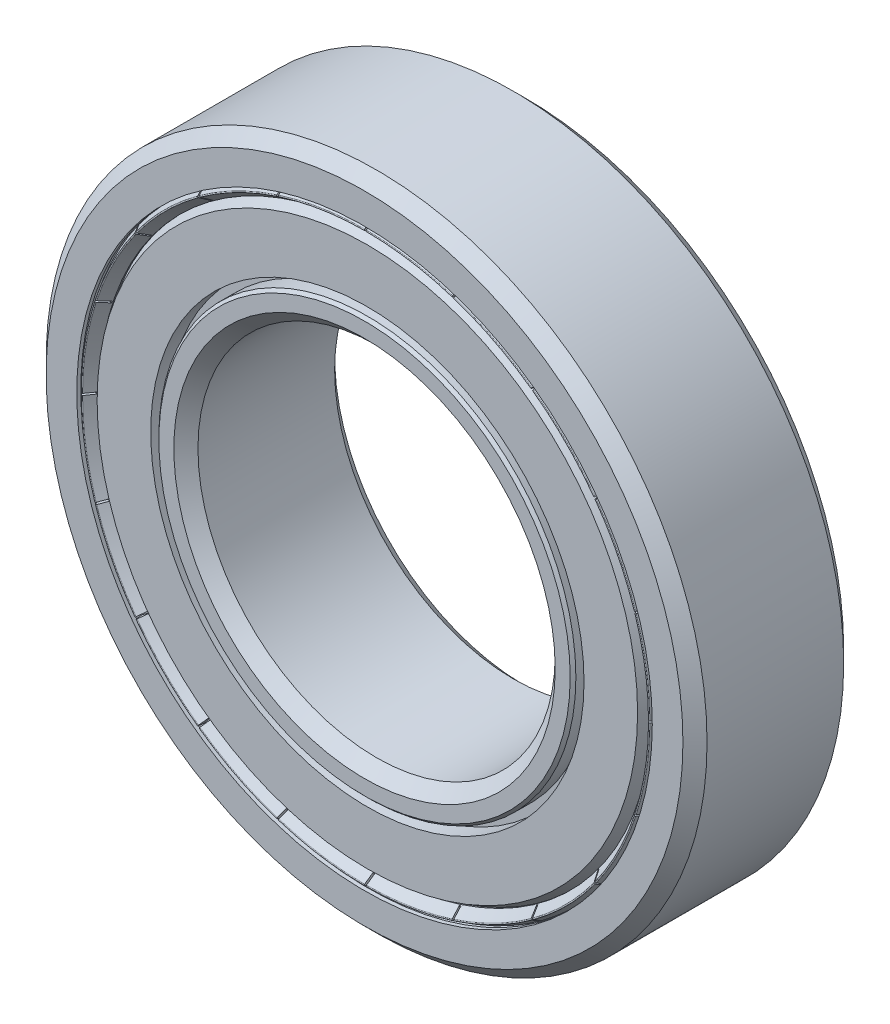
SolidWorks part; units mm, degrees
ref_plane "Front Plane" through (0, 0, 0) normal (0, 0, 1) x (1, 0, 0)
ref_plane "Top Plane" through (0, 0, 0) normal (0, 1, 0) x (1, 0, 0)
ref_plane "Right Plane" through (0, 0, 0) normal (1, 0, 0) x (0, 0, -1)
sketch "Sketch1" plane through (0, 0, 0) normal (0, 0, 1) x (1, 0, 0)
  circle A0 centre (0, 0) radius 10
  circle A1 centre (0, 0) radius 18.5
  dimension "OD" = 37
  dimension "ID" = 20
sketch "Sketch2" plane through (0, 0, 0) normal (1, 0, 0) x (0, 0, -1)
  line L0 (-4.5, 18.5) -> (4.5, 18.5)
  line L1 (-4.5, 10) -> (-4.5, -10) construction
  line L2 (4.5, 18.5) -> (4.5, -18.5) construction
  line L3 (-4.5, 0) -> (4.5, 0) construction
  line L6 (0, 18.5) -> (0, 10) construction
  circle A0 centre (0, 14.25) radius 2.975 construction
  point P8 (0, 18.5)
  dimension "Approx. Ball Dia." = 5.95
  dimension "Width" = 9
  dimension "For Shaft Diameter" = 20
  dimension "For Housing ID" = 37
sketch "Sketch3" plane through (0, 0, 0) normal (1, 0, 0) x (0, 0, -1)
  line L0 (0, 0) -> (0, 20) construction
  line L1 (-4.5, 10) -> (-4.5, -10) construction
  line L2 (3.825, 18.5) -> (-3.825, 18.5)
  line L3 (-3.825, 18.5) -> (-4.5, 17.825)
  line L4 (-4.5, 17.825) -> (-4.5, 16.1097)
  line L5 (-4.5, 16.1097) -> (-4.275, 16.1097)
  line L6 (-4.275, 16.1097) -> (-4.275, 16.6673)
  line L7 (-4.275, 16.6673) -> (-4.1159, 16.8264)
  line L8 (-4.1159, 16.8264) -> (-1.4875, 16.8264)
  line L10 (-4.5, 18.5) -> (4.5, 18.5) construction
  line L12 (-4.275, 16.6673) -> (-4.275, 17.225) construction
  line L13 (4.1159, 16.8264) -> (1.4875, 16.8264)
  line L14 (4.275, 16.6673) -> (4.1159, 16.8264)
  line L15 (4.275, 16.1097) -> (4.275, 16.6673)
  line L16 (4.5, 16.1097) -> (4.275, 16.1097)
  line L17 (4.5, 17.825) -> (4.5, 16.1097)
  line L18 (3.825, 18.5) -> (4.5, 17.825)
  line L19 (3.825, 10) -> (-3.825, 10)
  line L20 (-3.825, 10) -> (-4.5, 10.675)
  line L21 (-4.5, 10.675) -> (-4.5, 11.5145)
  line L22 (-4.5, 11.5145) -> (-4.3409, 11.6736)
  line L23 (-4.3409, 11.6736) -> (-1.4875, 11.6736)
  line L25 (4.3409, 11.6736) -> (1.4875, 11.6736)
  line L26 (4.5, 11.5145) -> (4.3409, 11.6736)
  line L27 (4.5, 10.675) -> (4.5, 11.5145)
  line L28 (3.825, 10) -> (4.5, 10.675)
  circle A2 centre (0, 14.25) radius 2.975 construction
  arc A3 (-1.4875, 16.8264) -> (1.4875, 16.8264) centre (0, 14.25) cw
  arc A4 (-1.4875, 11.6736) -> (1.4875, 11.6736) centre (0, 14.25) ccw
  point P5 (0, 17.225)
  point P31 (0, 18.5)
  point P37 (0, 10)
  dimension "D1" = 45
  dimension "D2" = 0.225
  dimension "D3" = 2.975
  dimension "D4" = 0.675
revolve "Revolve1" add sketch "Sketch3" angle 360 about L3
sketch "Sketch4" plane through (0, 0, 0) normal (1, 0, 0) x (0, 0, -1)
  line L0 (0, 17.225) -> (0, 11.275)
  line L1 (0, 18.5) -> (0, 10) construction
  circle A0 centre (0, 14.25) radius 2.975 construction
  arc A1 (0, 11.275) -> (0, 17.225) centre (0, 14.25) cw
revolve "Revolve2" add sketch "Sketch4" angle 360 about L6
pattern_circular "CirPattern1" count 10 over 360 about axis through (0, 0, 0) along (0, 0, 1) of bodies 106
sketch "Sketch5" plane through (0, 0, 0) normal (1, 0, 0) x (0, 0, -1)
  line L0 (-2.975, 14.25) -> (-2.975, 11.6736) construction
  line L1 (-4.3409, 11.6736) -> (-1.4875, 11.6736) construction
  line L3 (-2.975, 11.6736) -> (-3.4303, 11.6736)
  line L4 (-3.4303, 11.6736) -> (-3.4303, 12.1289)
  line L5 (-3.4303, 12.1289) -> (-4.3409, 12.1289)
  line L6 (-4.3409, 12.1289) -> (-4.3409, 15.1286)
  line L7 (-4.3409, 15.1286) -> (-3.4303, 15.6544)
  line L8 (-3.4303, 15.6544) -> (-2.975, 15.6544)
  line L9 (-2.975, 15.6544) -> (-2.975, 11.6736)
  line L10 (0, 14.25) -> (0, 18.5) construction
  line L11 (3.4303, 15.6544) -> (2.975, 15.6544)
  line L12 (4.3409, 15.1286) -> (3.4303, 15.6544)
  line L13 (4.3409, 12.1289) -> (4.3409, 15.1286)
  line L14 (3.4303, 12.1289) -> (4.3409, 12.1289)
  line L15 (3.4303, 11.6736) -> (3.4303, 12.1289)
  line L16 (2.975, 11.6736) -> (3.4303, 11.6736)
  line L17 (2.975, 15.6544) -> (2.975, 11.6736)
  line L18 (-4.3409, 15.1286) -> (-3.8856, 15.1286) construction
  line L19 (-3.8856, 15.1286) -> (-3.4303, 15.1286) construction
  line L20 (-3.4303, 15.1286) -> (-2.975, 15.1286) construction
  line L21 (-3.4303, 15.6544) -> (-3.4303, 16.1097) construction
  circle A0 centre (0, 14.25) radius 2.975 construction
  dimension "D1" = 30
revolve "Revolve3" add sketch "Sketch5" angle 360 about L3
sketch "Sketch6" plane through (0, 0, 0) normal (1, 0, 0) x (0, 0, -1)
  line L0 (-3.7517, 16.1097) -> (-4.1062, 16.1097)
  line L1 (-4.1062, 16.1097) -> (-4.5, 15.8823)
  line L2 (-4.5, 15.8823) -> (-3.8867, 15.4529)
  line L4 (-4.3409, 15.1286) -> (-3.4303, 15.6544) construction
  line L5 (-3.7517, 15.4688) -> (-3.7517, 16.1097)
  line L6 (-4.5, 16.1097) -> (-4.275, 16.1097) construction
  line L7 (-3.8867, 15.4529) -> (-3.8417, 15.4529)
  line L8 (-3.8417, 15.4529) -> (-3.7517, 15.4688)
  line L9 (-4.5, 17.825) -> (-4.5, -17.825) construction
  line L11 (-3.8417, 15.4529) -> (-3.7967, 15.4529) construction
  line L12 (-3.7967, 15.4529) -> (-3.7517, 15.4529) construction
  point P27 (-3.929, 16.1097)
  dimension "D1" = 30
  dimension "D3" = 10
  dimension "D2" = 35
  dimension "D4" = 0.045
  dimension "D5" = 0.3937
revolve "Revolve4" add sketch "Sketch6" angle 360 about L3
fillet "Fillet1" radius 0.045 1 edges at (15.8823, 0, 4.5)
sketch "Sketch7" plane through (0, 0, 0) normal (0, 0, 1) x (1, 0, 0)
  line L0 (-0.05, 16.1097) -> (-0.05, 16.2097)
  line L1 (-0.05, 16.1097) -> (0.05, 16.1097) construction
  line L2 (-0.05, 16.1097) -> (-0.05, 15.4529)
  line L3 (-0.05, 15.4529) -> (0.05, 15.4529) construction
  line L4 (0.05, 16.1097) -> (0.05, 15.4529)
  line L5 (-0.05, 16.2097) -> (0.05, 16.2097)
  line L6 (0.05, 16.2097) -> (0.05, 16.1097)
  line L7 (-0.05, 15.4529) -> (-0.05, 15.3529)
  line L8 (-0.05, 15.3529) -> (0.05, 15.3529)
  line L9 (0.05, 15.3529) -> (0.05, 15.4529)
  dimension "D1" = 0.1
extrude "Cut-Extrude1" cut sketch "Sketch7" along normal through all from vertex at 3.929 starting at point (0, 16.1097, 3.929)
pattern_circular "CirPattern2" count 20 over 360 about axis through (0, 0, 0) along (0, 0, 1) of "Cut-Extrude1"
mirror "Mirror1" about plane through (0, 0, 0) normal (0, 0, 1) of bodies 120
equation "\"Approx. Ball Dia.@Sketch2\"=( \"OD@Sketch1\" - \"ID@Sketch1\" )  * .5 * .7"
equation "\"D2@Sketch3\"=\"Width@Sketch2\"*.025"
equation "\"D3@Sketch3\"=\"Approx. Ball Dia.@Sketch2\"*.5"
equation "\"D4@Sketch3\"=\"Width@Sketch2\"*.075"
equation "\"Approx No of Balls\"= ( pi * \"OD@Sketch1\" ) * .5 / \"Approx. Ball Dia.@Sketch2\""
equation "\"D1@CirPattern1\"=\"Approx No of Balls\""
equation "\"D4@Sketch6\"=\"D2@Sketch3\"*.2"
equation "\"D1@CirPattern2\"=\"Approx No of Balls\"*2"
equation "\"D5@Sketch6\"=\"D2@Sketch3\"*1.75"
equation "\"D1@Fillet1\"=\"d4@sketch6\""
